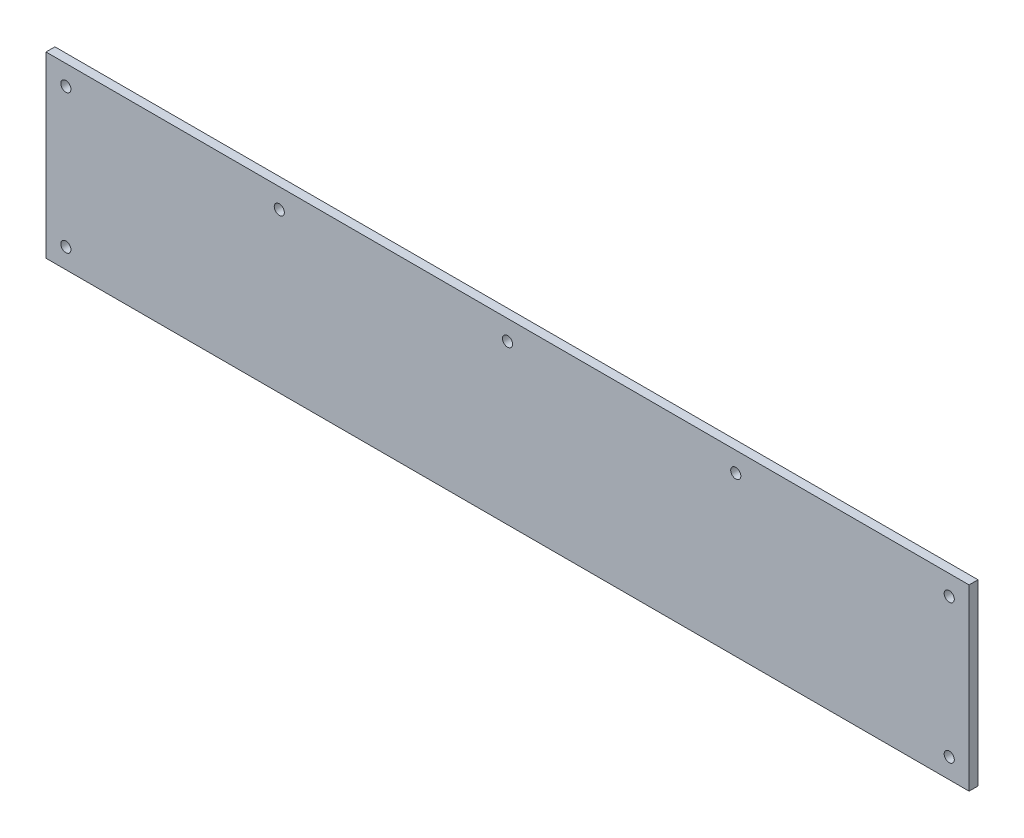
SolidWorks part; units mm, degrees
material "Acrylic (Medium-high impact)"
ref_plane "Front Plane" through (0, 0, 0) normal (0, 0, 1) x (1, 0, 0)
ref_plane "Top Plane" through (0, 0, 0) normal (0, 1, 0) x (1, 0, 0)
ref_plane "Right Plane" through (0, 0, 0) normal (1, 0, 0) x (0, 0, -1)
sketch "Sketch1" plane through (0, 0, 0) normal (0, 0, 1) x (1, 0, 0)
  line L0 (-222.5, 45) -> (-222.5, -45) construction
  line L1 (-232.5, -45) -> (232.5, -45)
  line L2 (-232.5, -45) -> (-232.5, 45)
  line L3 (-232.5, 45) -> (232.5, 45)
  line L4 (232.5, -45) -> (232.5, 45)
  line L5 (-232.5, -45) -> (232.5, 45) construction
  line L6 (-232.5, 45) -> (232.5, -45) construction
  line L7 (0, 45) -> (0, -45) construction
  line L8 (-232.5, 35) -> (2.55, 35) construction
  circle A0 centre (-222.5, 35) radius 2.55
  circle A1 centre (-222.5, -35) radius 2.55
  circle A2 centre (0, 35) radius 2.55
  circle A3 centre (-114.975, 35) radius 2.55
  circle A4 centre (222.5, -35) radius 2.55
  circle A5 centre (222.5, 35) radius 2.55
  circle A6 centre (114.975, 35) radius 2.55
  point P0 (0, 0)
  point P17 (-114.975, 35)
  dimension "D4" = 5.1
  dimension "D5" = 10
  dimension "D6" = 10
  dimension "D7" = 10
  dimension "D1" = 465
  dimension "D2" = 90
  dimension "D3" = 10
extrude "Boss-Extrude1" add sketch "Sketch1" along normal mid plane 4.4958
